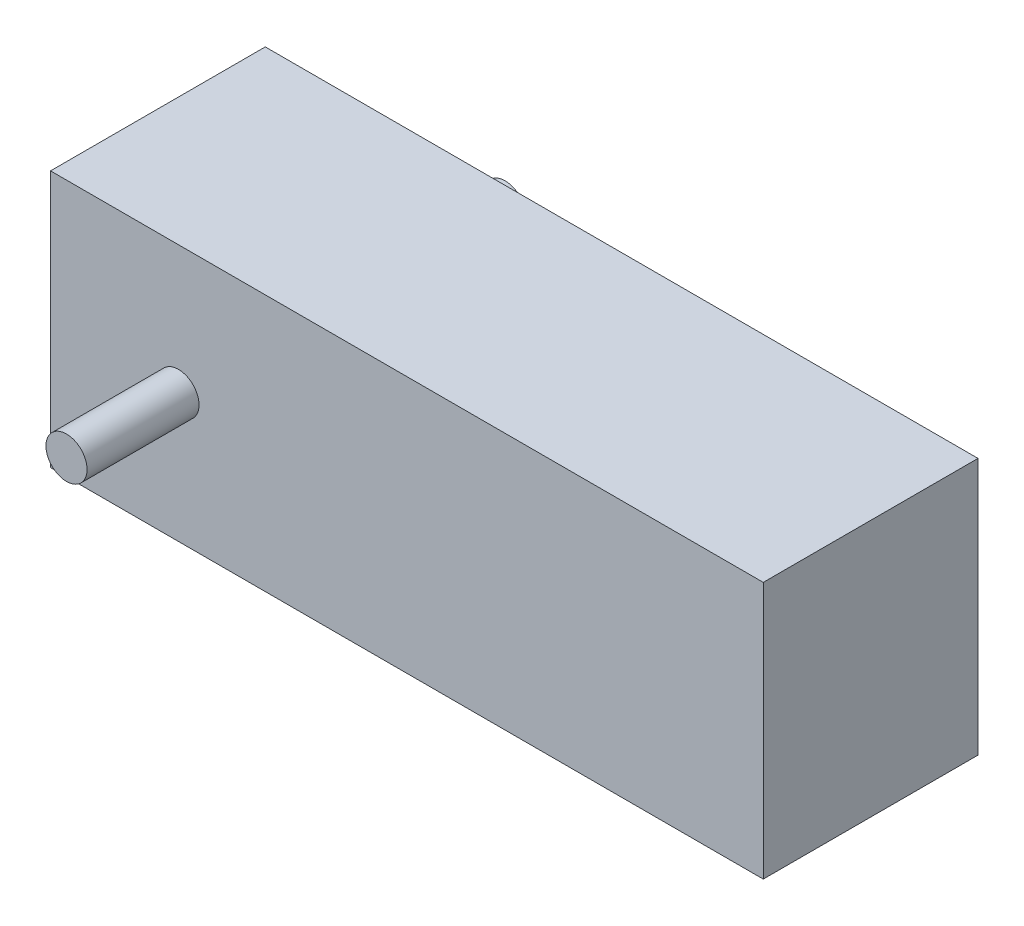
SolidWorks part; units mm, degrees
ref_plane "Front Plane" through (0, 0, 0) normal (0, 0, 1) x (1, 0, 0)
ref_plane "Top Plane" through (0, 0, 0) normal (0, 1, 0) x (1, 0, 0)
ref_plane "Right Plane" through (0, 0, 0) normal (1, 0, 0) x (0, 0, -1)
sketch "Sketch1" plane through (0, 0, 0) normal (0, 0, 1) x (1, 0, 0)
  line L1 (-31.2, 11.25) -> (31.2, 11.25)
  line L2 (-31.2, 11.25) -> (-31.2, -11.25)
  line L3 (-31.2, -11.25) -> (31.2, -11.25)
  line L4 (31.2, 11.25) -> (31.2, -11.25)
  line L5 (-31.2, 11.25) -> (31.2, -11.25) construction
  line L6 (-31.2, -11.25) -> (31.2, 11.25) construction
  point P0 (0, 0)
  dimension "D1" = 62.4
  dimension "D2" = 22.5
extrude "Boss-Extrude1" add sketch "Sketch1" along normal blind 18.8
sketch "Sketch2" plane through (0, 0, 18.8) normal (0, 0, 1) x (1, 0, 0)
  line L0 (-31.2, 0) -> (-20, 0) construction
  line L1 (-31.2, 11.25) -> (-31.2, -11.25) construction
  circle A0 centre (-20, 0) radius 1.8
extrude "Boss-Extrude2" add sketch "Sketch2" along normal blind 9.8
sketch "Sketch3" plane through (0, 0, 0) normal (0, 0, -1) x (-1, 0, 0)
  circle A0 centre (20, 0) radius 1.8
extrude "Boss-Extrude3" add sketch "Sketch3" along normal blind 9.8
